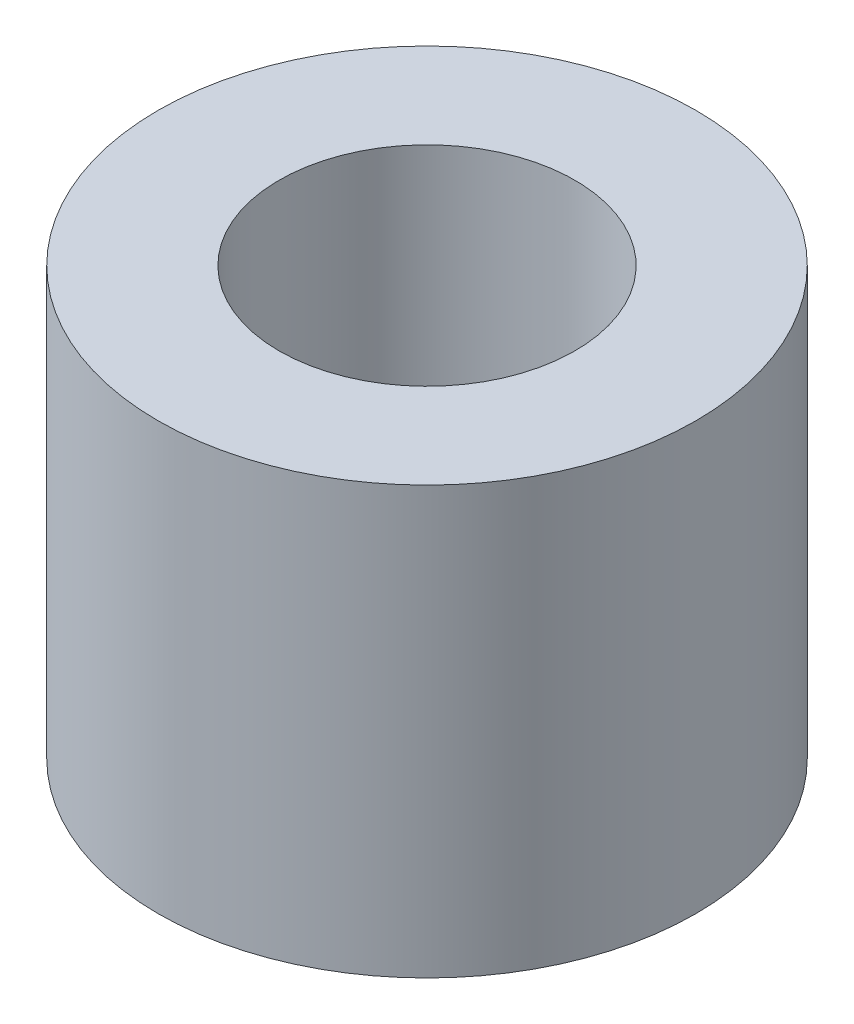
SolidWorks part; units mm, degrees
material "ABS"
ref_plane "Front" through (0, 0, 0) normal (0, 0, 1) x (1, 0, 0)
ref_plane "Top" through (0, 0, 0) normal (0, 1, 0) x (1, 0, 0)
ref_plane "Right" through (0, 0, 0) normal (1, 0, 0) x (0, 0, -1)
sketch "Sketch1" plane through (0, 0, 0) normal (0, 1, 0) x (1, 0, 0)
  circle A0 centre (0, 0) radius 2
  circle A1 centre (0, 0) radius 1.1
  dimension "D1" = 2.2
  dimension "D2" = 4
extrude "Boss-Extrude1" add sketch "Sketch1" along normal blind 3.175
